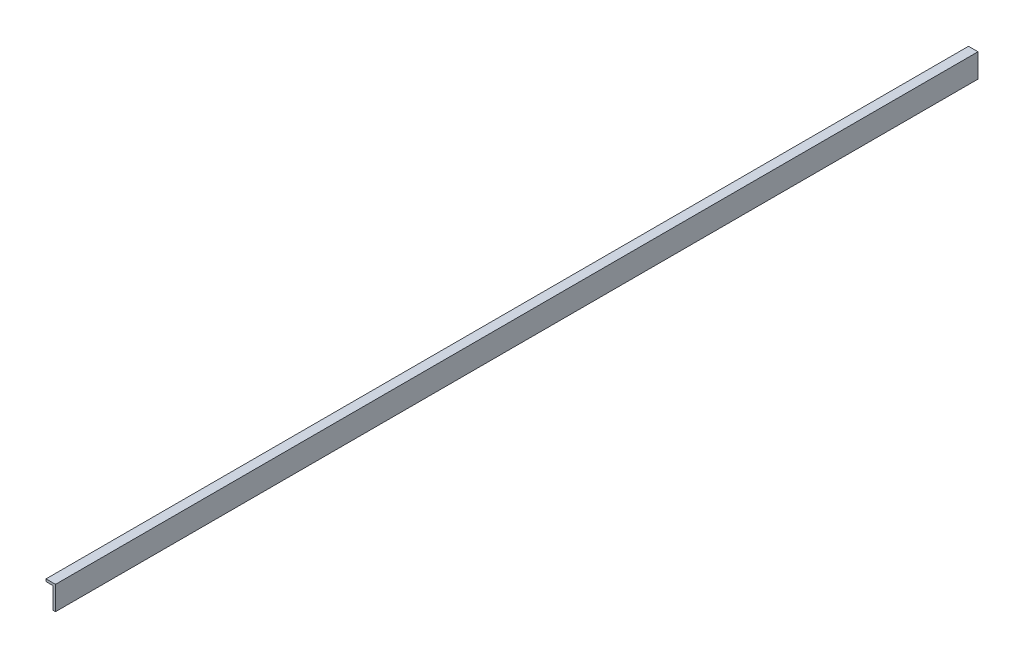
SolidWorks part; units mm, degrees
ref_plane "Front Plane" through (0, 0, 0) normal (0, 0, 1) x (1, 0, 0)
ref_plane "Top Plane" through (0, 0, 0) normal (0, 1, 0) x (1, 0, 0)
ref_plane "Right Plane" through (0, 0, 0) normal (1, 0, 0) x (0, 0, -1)
other "Configuration Table"
sketch "Sketch1" plane through (0, 0, 0) normal (0, 0, 1) x (1, 0, 0)
  line L0 (54, 0) -> (56, 0)
  line L1 (56, 0) -> (56, 20)
  line L2 (56, 20) -> (48, 20)
  line L3 (48, 20) -> (48, 18)
  line L4 (48, 18) -> (54, 18)
  line L5 (54, 18) -> (54, 0)
extrude "LRAF_sag_20x8x2_1" add sketch "Sketch1" against normal blind 777.5 from offset 20 separate body
